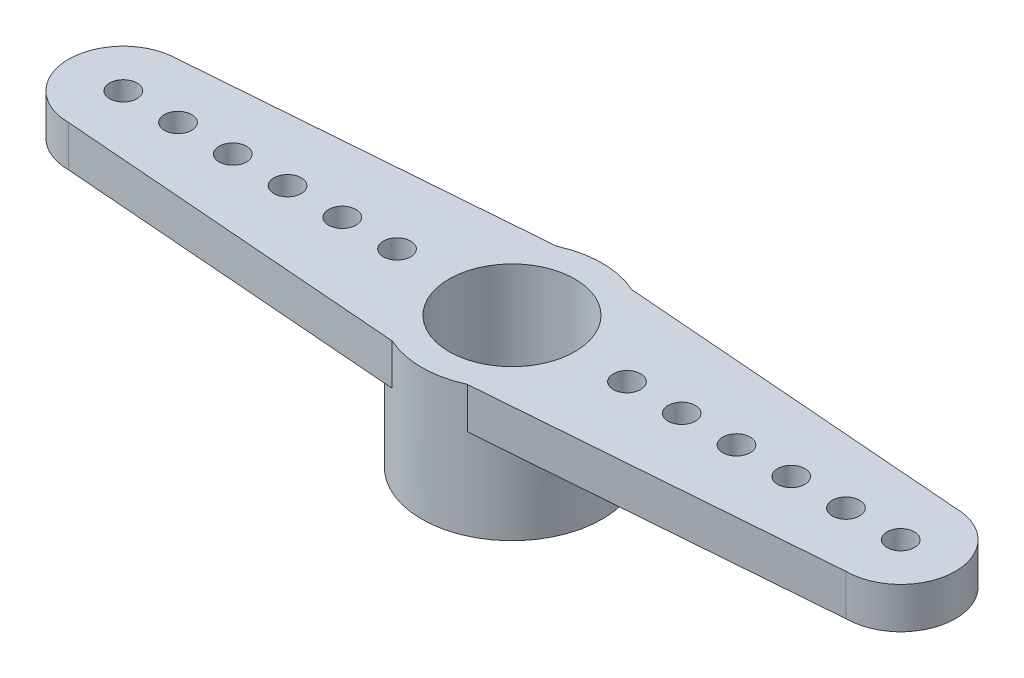
SolidWorks part; units mm, degrees
ref_plane "Plano frontal" through (0, 0, 0) normal (0, 0, 1) x (1, 0, 0)
ref_plane "Plano superior" through (0, 0, 0) normal (0, 1, 0) x (1, 0, 0)
ref_plane "Plano direito" through (0, 0, 0) normal (1, 0, 0) x (0, 0, -1)
sketch "Esboço2" plane through (0, 0, 0) normal (0, 1, 0) x (1, 0, 0)
  circle A0 centre (0, 0) radius 2.3
  circle A1 centre (0, 0) radius 3.3
extrude "Ressalto-extrusão1" add sketch "Esboço2" along normal blind 4.8
sketch "Esboço3" plane through (0, 4.8, 0) normal (0, 1, 0) x (1, 0, 0)
  line L3 (-1.3748, 3) -> (-14.2, 2)
  line L4 (-1.3748, -3) -> (-14.2, -2)
  line L6 (1.3748, -3) -> (14.2, -2)
  line L7 (1.3748, 3) -> (14.2, 2)
  circle A0 centre (0, 0) radius 3.3 construction
  arc A1 (14.2, -2) -> (14.2, 2) centre (14.2, 0) ccw
  circle A2 centre (14.2, 0) radius 0.5
  circle A3 centre (12.2, 0) radius 0.5
  circle A4 centre (10.2, 0) radius 0.5
  circle A5 centre (8.2, 0) radius 0.5
  circle A6 centre (6.2, 0) radius 0.5
  circle A7 centre (4.2, 0) radius 0.5
  circle A15 centre (-4.2, 0) radius 0.5
  circle A16 centre (-6.2, 0) radius 0.5
  circle A17 centre (-8.2, 0) radius 0.5
  circle A18 centre (-10.2, 0) radius 0.5
  circle A19 centre (-12.2, 0) radius 0.5
  circle A20 centre (-14.2, 0) radius 0.5
  arc A21 (-14.2, -2) -> (-14.2, 2) centre (-14.2, 0) cw
  circle M7 centre (0, 0) radius 3.3
extrude "Ressalto-extrusão2" add sketch "Esboço3" against normal blind 1.5 contours L6 A1 L7 A7 A6 A5 A4 A3 A2 M7 | A21 L4 L3 A19 A17 A15 A16 A18 A20 M7
